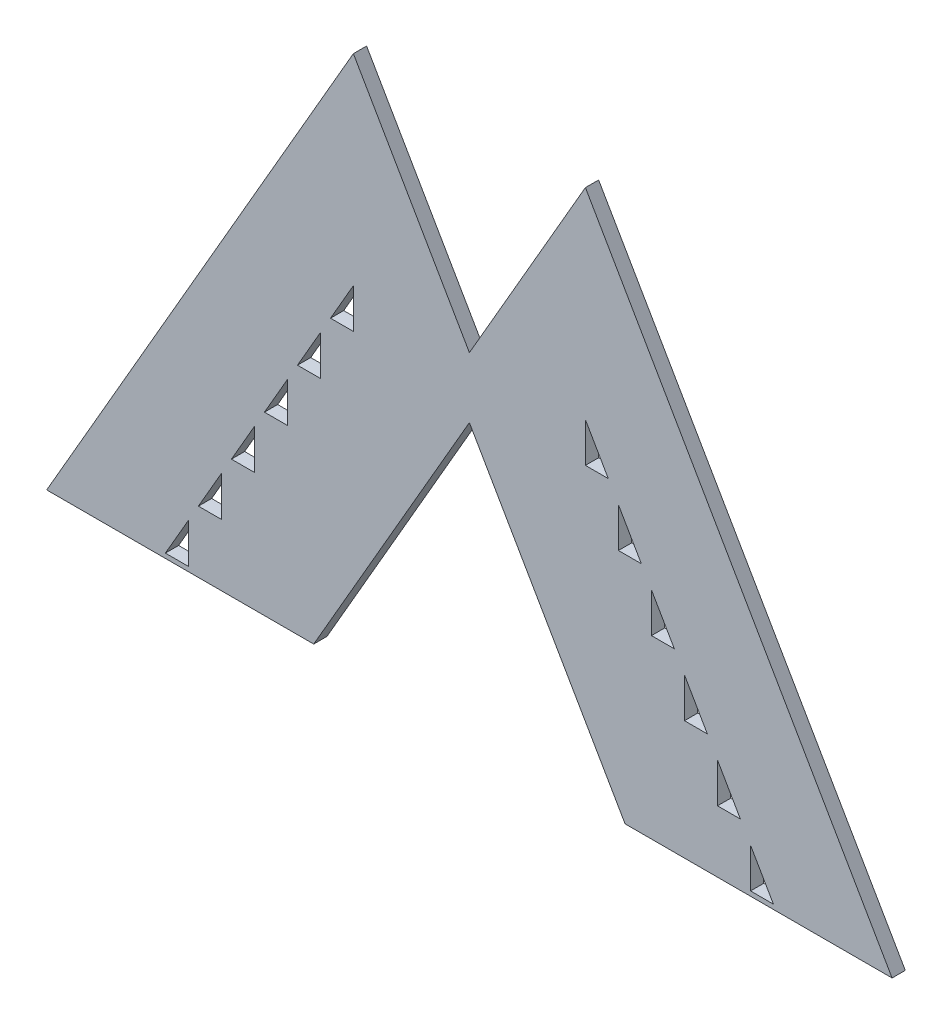
SolidWorks part; units mm, degrees
ref_plane "前视基准面" through (0, 0, 0) normal (0, 0, 1) x (1, 0, 0)
ref_plane "上视基准面" through (0, 0, 0) normal (0, 1, 0) x (1, 0, 0)
ref_plane "右视基准面" through (0, 0, 0) normal (1, 0, 0) x (0, 0, -1)
sketch "草图1" plane through (0, 0, 0) normal (0, 0, 1) x (1, 0, 0)
  line L0 (-32, 0) -> (32, 0)
  line L1 (-32, 0) -> (0, 55.4256) construction
  line L2 (0, 55.4256) -> (32, 0) construction
  line L3 (-54.92, 25) -> (63.5506, 25) construction
  line L4 (0, 55.4256) -> (0, 25) construction
  line L5 (-21.0105, 40.2128) -> (25.9522, 40.2128) construction
  line L6 (-8.7831, 40.2128) -> (0, 25)
  line L7 (0, 25) -> (8.7831, 40.2128)
  line L8 (-8.7831, 40.2128) -> (-32, 0)
  line L9 (8.7831, 40.2128) -> (32, 0)
  point P9 (0, 40.2128)
  dimension "D1" = 64
  dimension "D2" = 32
  dimension "D3" = 60
  dimension "D4" = 25
extrude "凸台-拉伸1" add sketch "草图1" along normal blind 1
sketch "草图2" plane through (0, 0, 1) normal (0, 0, 1) x (1, 0, 0)
  line L0 (-4.3916, 32.6064) -> (-23.7926, -0.9972) construction
  line L1 (0, 25) -> (-8.7831, 40.2128) construction
  line L2 (-8.7831, 40.2128) -> (-32, 0) construction
  line L3 (0, 25) -> (-27.0373, 25) construction
  line L4 (-8.7831, 25) -> (-10.5152, 22)
  line L5 (-10.5152, 22) -> (-8.7831, 22)
  line L6 (-8.7831, 22) -> (-8.7831, 25)
  line L7 (-11.2831, 17.6699) -> (-11.2831, 20.6699)
  line L8 (-11.2831, 20.6699) -> (-13.0152, 17.6699)
  line L9 (-13.0152, 17.6699) -> (-11.2831, 17.6699)
  line L10 (-13.7831, 13.3397) -> (-13.7831, 16.3397)
  line L11 (-13.7831, 16.3397) -> (-15.5152, 13.3397)
  line L12 (-15.5152, 13.3397) -> (-13.7831, 13.3397)
  line L13 (-16.2831, 9.0096) -> (-16.2831, 12.0096)
  line L14 (-16.2831, 12.0096) -> (-18.0152, 9.0096)
  line L15 (-18.0152, 9.0096) -> (-16.2831, 9.0096)
  line L16 (-18.7831, 4.6795) -> (-18.7831, 7.6795)
  line L17 (-18.7831, 7.6795) -> (-20.5152, 4.6795)
  line L18 (-20.5152, 4.6795) -> (-18.7831, 4.6795)
  line L19 (-21.2831, 0.3494) -> (-21.2831, 3.3494)
  line L20 (-21.2831, 3.3494) -> (-23.0152, 0.3494)
  line L21 (-23.0152, 0.3494) -> (-21.2831, 0.3494)
  line L22 (-8.7831, 22) -> (-11.2831, 17.6699) construction
  line L23 (0, -0.55) -> (0, 0.55) construction
  line L24 (23.0152, 0.3494) -> (21.2831, 0.3494)
  line L25 (21.2831, 3.3494) -> (23.0152, 0.3494)
  line L26 (21.2831, 0.3494) -> (21.2831, 3.3494)
  line L27 (20.5152, 4.6795) -> (18.7831, 4.6795)
  line L28 (18.7831, 7.6795) -> (20.5152, 4.6795)
  line L29 (18.7831, 4.6795) -> (18.7831, 7.6795)
  line L30 (18.0152, 9.0096) -> (16.2831, 9.0096)
  line L31 (16.2831, 12.0096) -> (18.0152, 9.0096)
  line L32 (16.2831, 9.0096) -> (16.2831, 12.0096)
  line L33 (15.5152, 13.3397) -> (13.7831, 13.3397)
  line L34 (13.7831, 16.3397) -> (15.5152, 13.3397)
  line L35 (13.7831, 13.3397) -> (13.7831, 16.3397)
  line L36 (13.0152, 17.6699) -> (11.2831, 17.6699)
  line L37 (11.2831, 20.6699) -> (13.0152, 17.6699)
  line L38 (11.2831, 17.6699) -> (11.2831, 20.6699)
  line L39 (10.5152, 22) -> (8.7831, 22)
  line L40 (8.7831, 25) -> (10.5152, 22)
  line L41 (8.7831, 22) -> (8.7831, 25)
  dimension "D1" = 3
  dimension "D3" = 5
  dimension "D2" = 6
extrude "切除-拉伸1" cut sketch "草图2" against normal through all
sketch "草图3" plane through (0, 0, 1) normal (0, 0, 1) x (1, 0, 0)
  line L0 (-11.7853, 0) -> (0, 20.4128)
  line L2 (0, 20.4128) -> (11.7853, 0)
  line L3 (11.7853, 0) -> (-11.7853, 0)
  line L4 (-8.7831, 40.2128) -> (-32, 0) construction
  line L5 (32, 0) -> (8.7831, 40.2128) construction
  line L7 (-41.291, 5.2) -> (41.9302, 5.2) construction
  line L8 (-32, 0) -> (32, 0) construction
  line L9 (-8.7831, 22) -> (-8.7831, 5.2) construction
  point P11 (-12.395, -1.056)
  dimension "D1" = 5.2
extrude "切除-拉伸2" cut sketch "草图3" against normal blind 10
